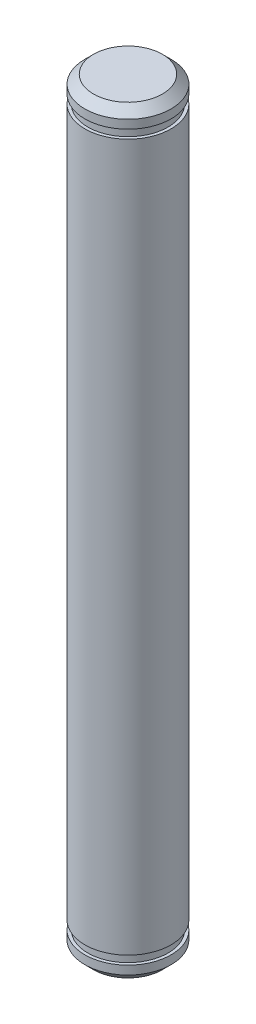
SolidWorks part; units mm, degrees
ref_plane "前视基准面" through (0, 0, 0) normal (0, 0, 1) x (1, 0, 0)
ref_plane "上视基准面" through (0, 0, 0) normal (0, 1, 0) x (1, 0, 0)
ref_plane "右视基准面" through (0, 0, 0) normal (1, 0, 0) x (0, 0, -1)
other "Configuration Table"
sketch "草图1" plane through (0, 0, 0) normal (0, 0, 1) x (1, 0, 0)
  line L0 (0, 61.8249) -> (0, -44.5084) construction
  line L1 (0, 44) -> (5, 44)
  line L2 (5, 44) -> (5, 29)
  line L6 (5, -29) -> (5, -44)
  line L7 (5, -44) -> (0, -44)
  line L8 (0, 0) -> (41.6667, 0) construction
  line L9 (0, 44) -> (0, -44)
  line L10 (5, 29) -> (5, -29)
  dimension "D1" = 5
  dimension "D2" = 5
  dimension "D5" = 88
revolve "旋转1" add sketch "草图1" angle 360 about L9
chamfer "倒角1" distance 1 angle 45 2 edges at (-5, -44, 0) (-5, 44, 0)
ref_plane "基准面1" through (0, 0, 0) normal (0, 1, 0) x (1, 0, 0)
sketch "草图2" plane through (0, 44, 0) normal (0, 1, 0) x (1, 0, 0)
  circle A0 centre (0, 0) radius 5 construction
  circle A1 centre (0, 0) radius 5
  circle A2 centre (0, 0) radius 4.65
  dimension "D1" = 9.3
extrude "切除-拉伸1" cut sketch "草图2" along normal blind 1 from offset 3 offset against normal yes
mirror "镜向1" about plane through (0, 0, 0) normal (0, 1, 0) of "切除-拉伸1"
